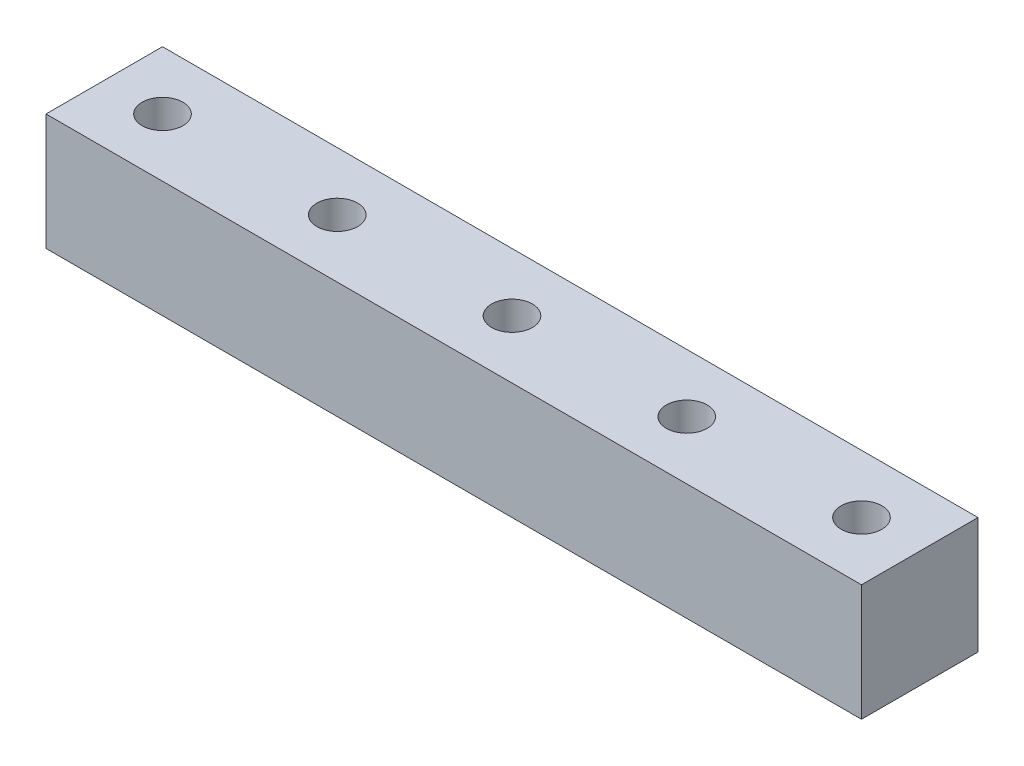
SolidWorks part; units mm, degrees
material "HDPE, Black"
ref_plane "Front Plane" through (0, 0, 0) normal (0, 0, 1) x (1, 0, 0)
ref_plane "Top Plane" through (0, 0, 0) normal (0, 1, 0) x (1, 0, 0)
ref_plane "Right Plane" through (0, 0, 0) normal (1, 0, 0) x (0, 0, -1)
sketch "Sketch1" plane through (0, 0, 0) normal (0, 1, 0) x (1, 0, 0)
  line L0 (-60, 0) -> (-30, 0) construction
  line L1 (-70, -10) -> (70, -10)
  line L2 (-70, -10) -> (-70, 10)
  line L3 (-70, 10) -> (70, 10)
  line L4 (70, -10) -> (70, 10)
  line L5 (-70, -10) -> (70, 10) construction
  line L6 (-70, 10) -> (70, -10) construction
  line L7 (-30, 0) -> (0, 0) construction
  line L8 (0, 0) -> (30, 0) construction
  line L9 (30, 0) -> (60, 0) construction
  circle A0 centre (-60, 0) radius 3.5
  circle A1 centre (-30, 0) radius 3.5
  circle A2 centre (0, 0) radius 3.5
  circle A3 centre (30, 0) radius 3.5
  circle A4 centre (60, 0) radius 3.5
  point P0 (0, 0)
  dimension "D4" = 7
  dimension "D1" = 20
  dimension "D2" = 140
  dimension "D3" = 30
extrude "Boss-Extrude1" add sketch "Sketch1" along normal blind 20
